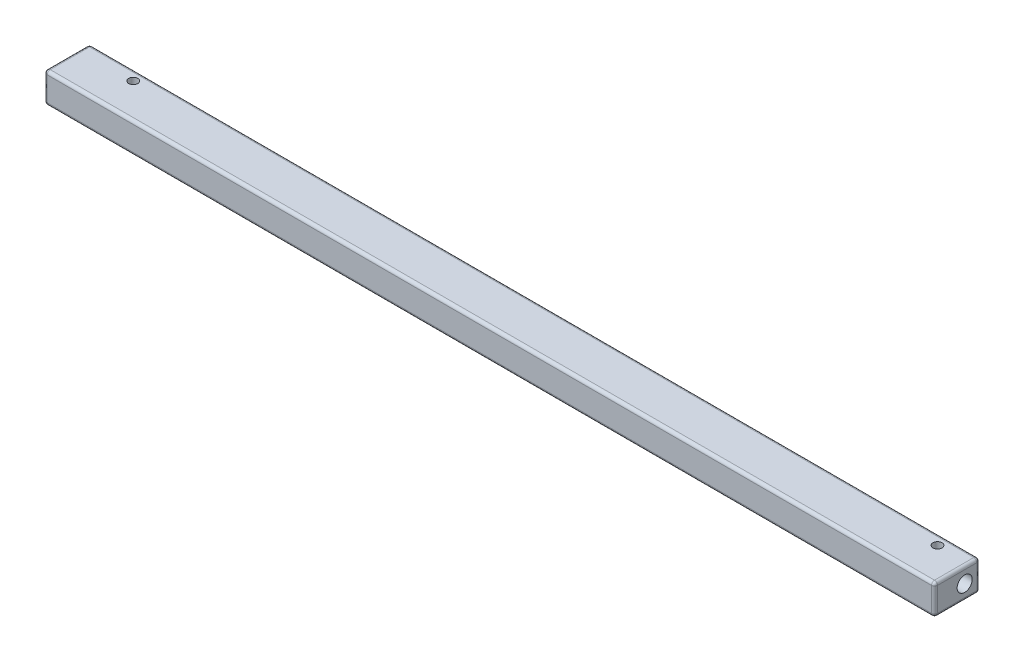
SolidWorks part; units mm, degrees
material "1023 Carbon Steel Sheet (SS)"
ref_plane "Ön Düzlem" through (0, 0, 0) normal (0, 0, 1) x (1, 0, 0)
ref_plane "Üst Düzlem" through (0, 0, 0) normal (0, 1, 0) x (1, 0, 0)
ref_plane "Sağ Düzlem" through (0, 0, 0) normal (1, 0, 0) x (0, 0, -1)
sketch "Sketch1" plane through (0, 0, 0) normal (0, 0, 1) x (1, 0, 0)
  line L0 (-295, 0) -> (295, 0)
  line L1 (295, 0) -> (295, 20)
  line L2 (295, 20) -> (-295, 20)
  line L3 (-295, 20) -> (-295, 0)
  dimension "D1" = 590
  dimension "D2" = 20
extrude "Boss-Extrude1" add sketch "Sketch1" along normal blind 30
fillet "Fillet1" radius 2 12 edges at (-295, 0, 15) (-295, 10, 0) (0, 0, 0) (-295, 20, 15) (0, 20, 0) (295, 10, 0) (295, 0, 15) (295, 20, 15) (-295, 10, 30) (295, 10, 30) (0, 0, 30) (0, 20, 30)
sketch "Sketch6" plane through (295, 0, 0) normal (1, 0, 0) x (0, 0, -1)
  line L1 (-28, 20) -> (-2, 20) construction
  line L2 (0, 18) -> (0, 2) construction
  circle A0 centre (-10, 10) radius 5
  dimension "D1" = 10
  dimension "D3" = 10
  dimension "D2" = 10
extrude "Cut-Extrude5" cut sketch "Sketch6" against normal blind 8
sketch "Sketch7" plane through (-295, 0, 0) normal (-1, 0, 0) x (0, 0, 1)
  line L1 (2, 20) -> (28, 20) construction
  line L2 (30, 18) -> (30, 2) construction
  circle A0 centre (15, 10) radius 5
  dimension "D1" = 15
  dimension "D3" = 10
  dimension "D2" = 10
extrude "Cut-Extrude6" cut sketch "Sketch7" against normal blind 8
sketch "Sketch8" plane through (0, 0, 0) normal (0, -1, 0) x (1, 0, 0)
  line L2 (0, 0) -> (0, 28) construction
  line L3 (293, 28) -> (-293, 28) construction
  line L4 (-293, 28) -> (-293, 2) construction
  line L5 (-293, 30) -> (293, 30) construction
  line L6 (293, 2) -> (293, 28) construction
  circle A1 centre (-259, 7) radius 3
  circle A2 centre (274, 7) radius 3
  point P15 (293, 15)
  dimension "D1" = 34
  dimension "D3" = 6
  dimension "D4" = 19
  dimension "D5" = 6
  dimension "D2" = 23
  dimension "D6" = 23
extrude "Cut-Extrude7" cut sketch "Sketch8" against normal through all
